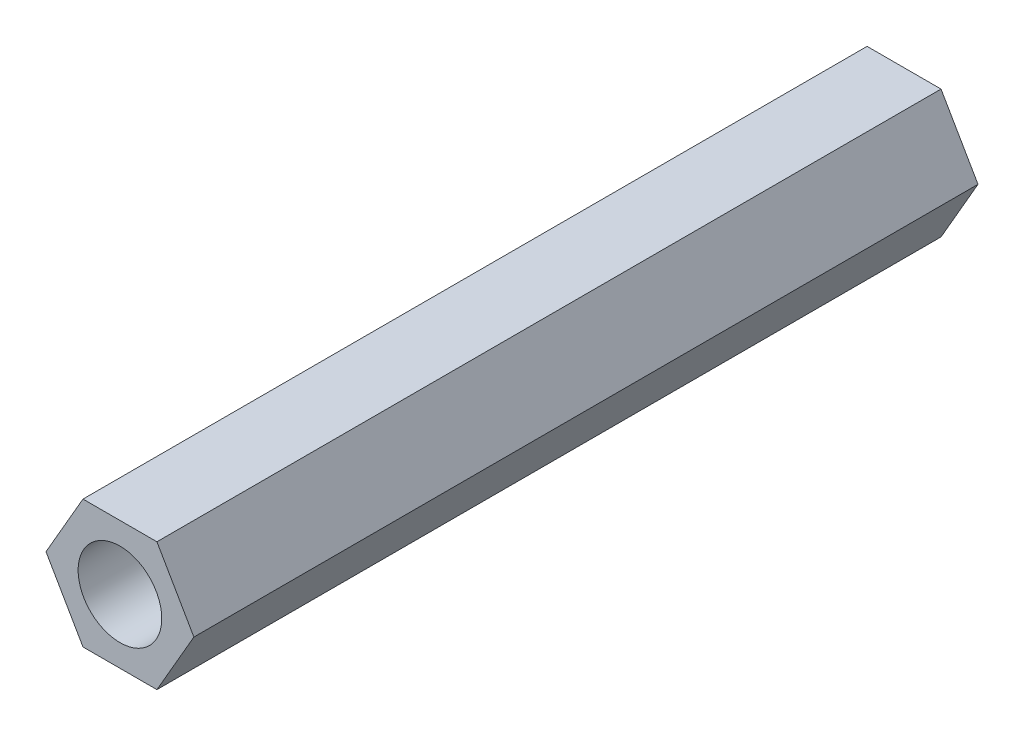
SolidWorks part; units mm, degrees
material "黄铜"
ref_plane "前视基准面" through (0, 0, 0) normal (0, 0, 1) x (1, 0, 0)
ref_plane "上视基准面" through (0, 0, 0) normal (0, 1, 0) x (1, 0, 0)
ref_plane "右视基准面" through (0, 0, 0) normal (1, 0, 0) x (0, 0, -1)
sketch "草图1" plane through (0, 0, 0) normal (0, 0, 1) x (1, 0, 0)
  line L1 (2.829, 0) -> (1.4145, 2.45)
  line L2 (1.4145, 2.45) -> (-1.4145, 2.45)
  line L3 (-1.4145, 2.45) -> (-2.829, 0)
  line L4 (-2.829, 0) -> (-1.4145, -2.45)
  line L5 (-1.4145, -2.45) -> (1.4145, -2.45)
  line L6 (1.4145, -2.45) -> (2.829, 0)
  circle A0 centre (0, 0) radius 1.6
  circle A1 centre (0, 0) radius 2.45 construction
  dimension "D1" = 3.2
  dimension "D2" = 4.9
extrude "凸台-拉伸1" add sketch "草图1" along normal blind 30
